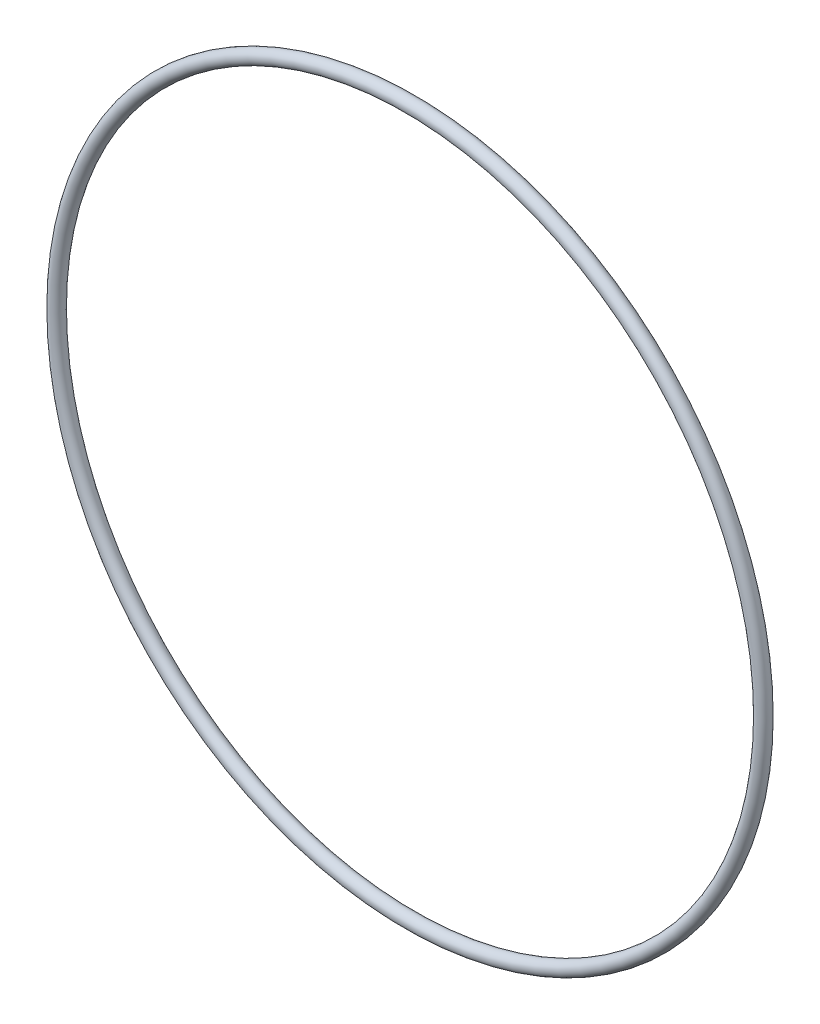
SolidWorks part; units mm, degrees
ref_plane "Front" through (0, 0, 0) normal (0, 0, 1) x (1, 0, 0)
ref_plane "Top" through (0, 0, 0) normal (0, 1, 0) x (1, 0, 0)
ref_plane "Right" through (0, 0, 0) normal (1, 0, 0) x (0, 0, -1)
sketch "Sketch1" plane through (0, 0, 0) normal (1, 0, 0) x (0, -1, 0)
  line L0 (0, -0.889) -> (0, 0.889) construction
  line L2 (-50.6971, 0) -> (50.6971, 0) construction
  line L3 (-44.3103, 0) -> (44.3103, 0) construction
  circle A0 centre (45.1993, 0) radius 0.889
  point P9 (44.3103, 0)
  point P10 (46.0883, 0)
  point P13 (45.1993, 0.889)
  point P14 (45.1993, -0.889)
  dimension "Width" = 1.778
  dimension "ID" = 88.6206
revolve "Revolve1" add sketch "Sketch1" angle 360 about L0
